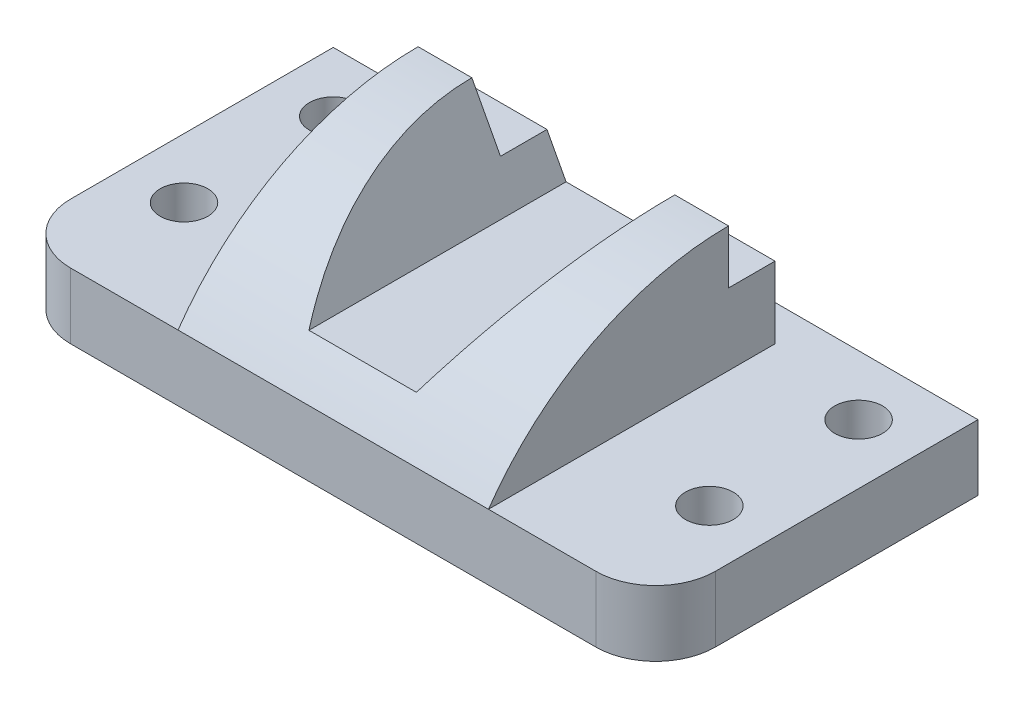
SolidWorks part; units mm, degrees
ref_plane "Front Plane" through (0, 0, 0) normal (0, 0, 1) x (1, 0, 0)
ref_plane "Top Plane" through (0, 0, 0) normal (0, 1, 0) x (1, 0, 0)
ref_plane "Right Plane" through (0, 0, 0) normal (1, 0, 0) x (0, 0, -1)
sketch "Sketch1" plane through (0, 0, 0) normal (0, 0, 1) x (1, 0, 0)
  line L0 (0, 0) -> (0, 32) construction
  line L1 (-54, 0) -> (54, 0)
  line L2 (-54, 0) -> (-54, 11)
  line L3 (-54, 11) -> (54, 11)
  line L4 (54, 0) -> (54, 11)
  line L5 (-26, 11) -> (-26, 32)
  line L6 (-26, 32) -> (-17, 32)
  line L7 (-17, 32) -> (-9, 17)
  line L8 (-9, 17) -> (9, 17)
  line L9 (26, 11) -> (26, 32)
  line L10 (26, 32) -> (17, 32)
  line L11 (17, 32) -> (9, 17)
  circle A0 centre (0, 32) radius 15
  point P4 (0, 0)
  point P12 (0, 0)
  point P15 (-11.0592, 17.2004)
  point P16 (0, 0)
  point P17 (0, 58.4464)
  point P18 (0, 0)
  point P19 (0, 0)
  point P24 (0, 17)
  dimension "D3" = 21
  dimension "D5" = 30
  dimension "D6" = 52
  dimension "D1" = 108
  dimension "D2" = 11
  dimension "D4" = 6
  dimension "D7" = 18
extrude "Boss-Extrude1" add sketch "Sketch1" along normal mid plane 54 contours L1 L0 L3 L2 | L3 L0 L8 L7 L6 L5 | L0 L1 L4 L3 | L0 L3 L9 L10 L11 L8
sketch "Sketch2" plane through (54, 0, 0) normal (1, 0, 0) x (0, 0, -1)
  line L0 (-27, 11) -> (27, 11)
  line L1 (21, 11) -> (21, 23)
  line L2 (21, 23) -> (13.2119, 23)
  line L3 (13.2119, 23) -> (13.2119, 32)
  line L4 (-27, 32) -> (27, 32) construction
  line L5 (27, 11) -> (27, 32) construction
  line L6 (-27, 11) -> (-27, 32)
  line L7 (-27, 32) -> (27, 32)
  line L8 (27, 32) -> (27, 11)
  arc A0 (13.2119, 32) -> (-27, 11) centre (13.2119, -17) ccw
  point P18 (27, 32)
  line M2 (27, 11) -> (-27, 11)
  dimension "D1" = 49
  dimension "D2" = 12
  dimension "D3" = 6
extrude "Cut-Extrude1" cut sketch "Sketch2" against normal through all contours A0 L7 L6 | L8 L7 L3 L2 L1 M2
sketch "Sketch3" plane through (0, 11, 0) normal (0, 1, 0) x (1, 0, 0)
  line L0 (0, 0) -> (0, -22.8099) construction
  line L1 (-54, -27) -> (-54, 27) construction
  line L2 (-54, 27) -> (54, 27) construction
  circle A0 centre (-44, 17) radius 4
  circle A1 centre (-44, -8) radius 4
  circle A2 centre (44, -8) radius 4
  circle A3 centre (44, 17) radius 4
  dimension "D1" = 8
  dimension "D2" = 10
  dimension "D3" = 10
  dimension "D5" = 25
  dimension "D4" = 2
extrude "Cut-Extrude2" cut sketch "Sketch3" against normal through all
fillet "Fillet1" radius 10 2 edges at (54, 5.5, 27) (-54, 5.5, 27)
